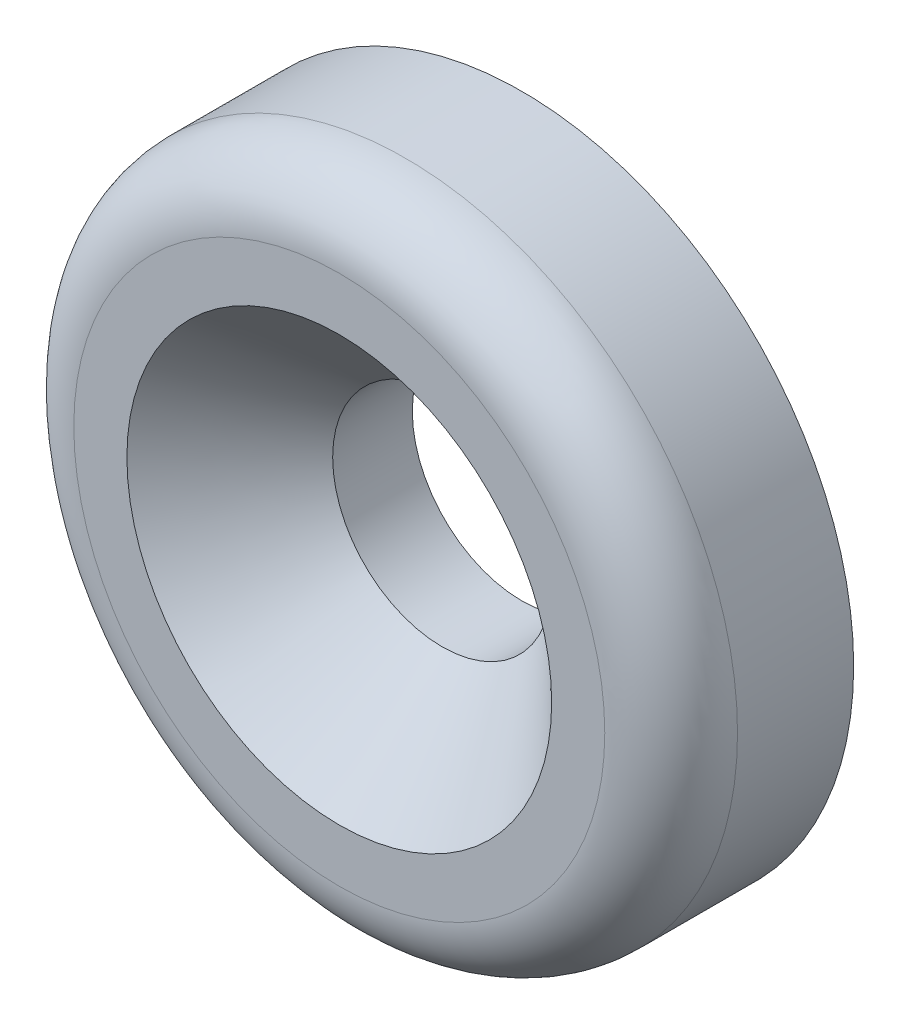
SolidWorks part; units mm, degrees
ref_plane "Front Plane" through (0, 0, 0) normal (1, 0, 0) x (0, 1, 0)
ref_plane "Top Plane" through (0, 0, 0) normal (0, 0, 1) x (0, 1, 0)
ref_plane "Right Plane" through (0, 0, 0) normal (0, 1, 0) x (-1, 0, 0)
sketch "Sketch1" plane through (0, 0, 0) normal (0, 0, 1) x (0, 1, 0)
  circle A0 centre (0, 0) radius 5
  circle A1 centre (0, 0) radius 1.65
  dimension "D1" = 10
  dimension "D2" = 3.3
extrude "Boss-Extrude1" add sketch "Sketch1" along normal blind 2.75
chamfer "Chamfer2" distance 1.55 angle 45 1 edges at (1.65, 0, 2.75)
fillet "Fillet1" radius 1 1 edges at (5, 0, 2.75)
